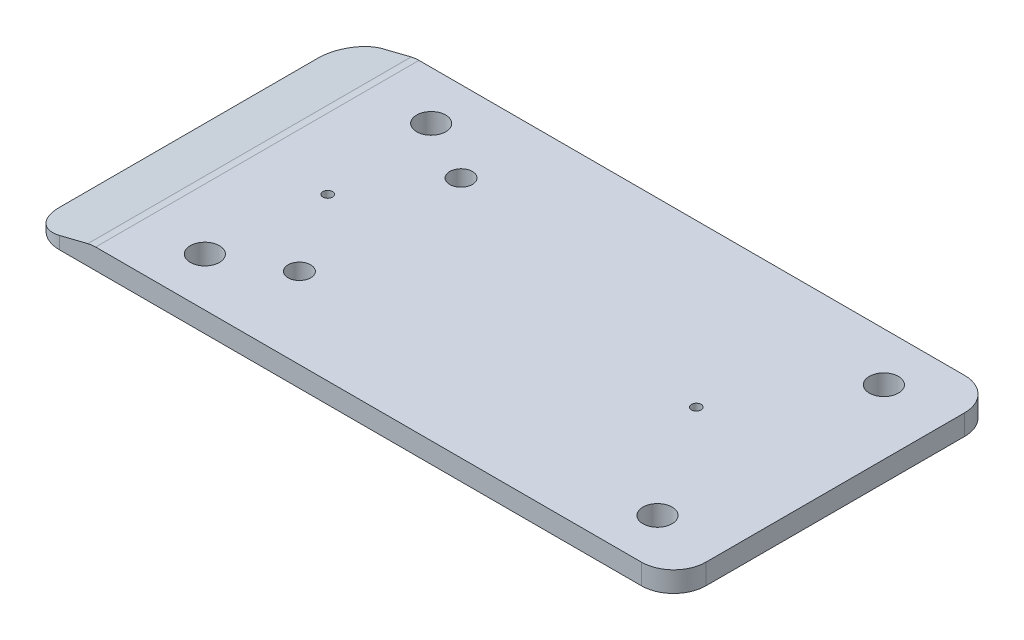
SolidWorks part; units mm, degrees
ref_plane "Front Plane" through (0, 0, 0) normal (0, 0, 1) x (1, 0, 0)
ref_plane "Top Plane" through (0, 0, 0) normal (0, 1, 0) x (1, 0, 0)
ref_plane "Right Plane" through (0, 0, 0) normal (1, 0, 0) x (0, 0, -1)
sketch "Sketch1" plane through (0, 0, 0) normal (0, 1, 0) x (1, 0, 0)
  line L1 (-100, -50) -> (100, -50)
  line L2 (-100, -50) -> (-100, 50)
  line L3 (-100, 50) -> (100, 50)
  line L4 (100, -50) -> (100, 50)
  line L5 (-100, -50) -> (100, 50) construction
  line L6 (-100, 50) -> (100, -50) construction
  point P0 (0, 0)
  dimension "D1" = 200
  dimension "D2" = 100
extrude "Boss-Extrude1" add sketch "Sketch1" along normal blind 6.35
chamfer "Chamfer1" distance 5 distance2 20 1 edges at (-100, 6.35, 0)
fillet "Fillet1" radius 10 5 edges at (-100, 0.675, -50) (100, 3.175, -50) (100, 3.175, 50) (-100, 0.675, 50) (-80, 6.35, 0)
hole_wizard "Ø3.0mm Dowel Hole1" positions "Sketch2" profile "Sketch4" hole size "Ø3.0" standard "ANSI Metric" end condition through all
sketch "Sketch2" plane through (0, 6.35, 0) normal (0, 1, 0) x (1, 0, 0)
  line L2 (0, 0) -> (57, 0) construction
  line L4 (0, 0) -> (-57, 0) construction
  point P8 (57, 0)
  point P13 (-57, 0)
  dimension "D1" = 114
sketch "Sketch4" plane through (-57, 6.35, 0) normal (1, 0, 0) x (0, 0, 1)
  line L0 (0, 0) -> (0, 6.35)
  line L1 (0, 6.35) -> (1.5, 6.35)
  line L2 (1.5, 6.35) -> (1.5, 0)
  line L5 (1.5, 0) -> (0, 0)
  line L11 (0, -6.35) -> (0, 107.95) construction
  dimension "Thru Hole Dia." = 3
  dimension "Thru Hole Depth" = 6.35
hole_wizard "M8 Clearance Hole1" positions "Sketch5" profile "Sketch6" hole size "M8" standard "ANSI Metric" end condition through all
sketch "Sketch5" plane through (0, 6.35, 0) normal (0, 1, 0) x (1, 0, 0)
  line L2 (-60, 35) -> (80, 35)
  line L3 (-60, 35) -> (-60, -35)
  line L4 (-60, -35) -> (80, -35)
  line L5 (80, 35) -> (80, -35)
  line L6 (100, -40) -> (100, 40) construction
  point P247 (-60, 35)
  point P248 (80, -35)
  point P409 (-60, -35)
  point P410 (80, 35)
  point P412 (-60, 0)
  dimension "D1" = 70
  dimension "D2" = 140
  dimension "D3" = 20
sketch "Sketch6" plane through (-60, 6.35, -35) normal (1, 0, 0) x (0, 0, 1)
  line L0 (0, 0) -> (0, 6.35)
  line L1 (0, 6.35) -> (4.5, 6.35)
  line L2 (4.5, 6.35) -> (4.5, 0)
  line L5 (4.5, 0) -> (0, 0)
  line L11 (0, -6.35) -> (0, 107.95) construction
  dimension "Thru Hole Dia." = 9
  dimension "Thru Hole Depth" = 6.35
hole_wizard "Ø6.0mm Dowel Hole1" positions "Sketch7" profile "Sketch8" hole size "Ø6.0" standard "ANSI Metric" end condition through all
sketch "Sketch7" plane through (0, 6.35, 0) normal (0, 1, 0) x (1, 0, 0)
  line L0 (-40.7689, 25) -> (-40.7689, -25) construction
  line L2 (-78.7689, 50) -> (-78.7689, -50) construction
  point P0 (-40.7689, 25)
  point P2 (-40.7689, -25)
  point P9 (-40.7689, 0)
  dimension "D1" = 38
  dimension "D2" = 50
sketch "Sketch8" plane through (-40.7689, 6.35, -25) normal (1, 0, 0) x (0, 0, 1)
  line L0 (0, 0) -> (0, 6.35)
  line L1 (0, 6.35) -> (3.5, 6.35)
  line L2 (3.5, 6.35) -> (3.5, 0)
  line L5 (3.5, 0) -> (0, 0)
  line L11 (0, -6.35) -> (0, 107.95) construction
  dimension "Thru Hole Dia." = 7
  dimension "Thru Hole Depth" = 6.35
